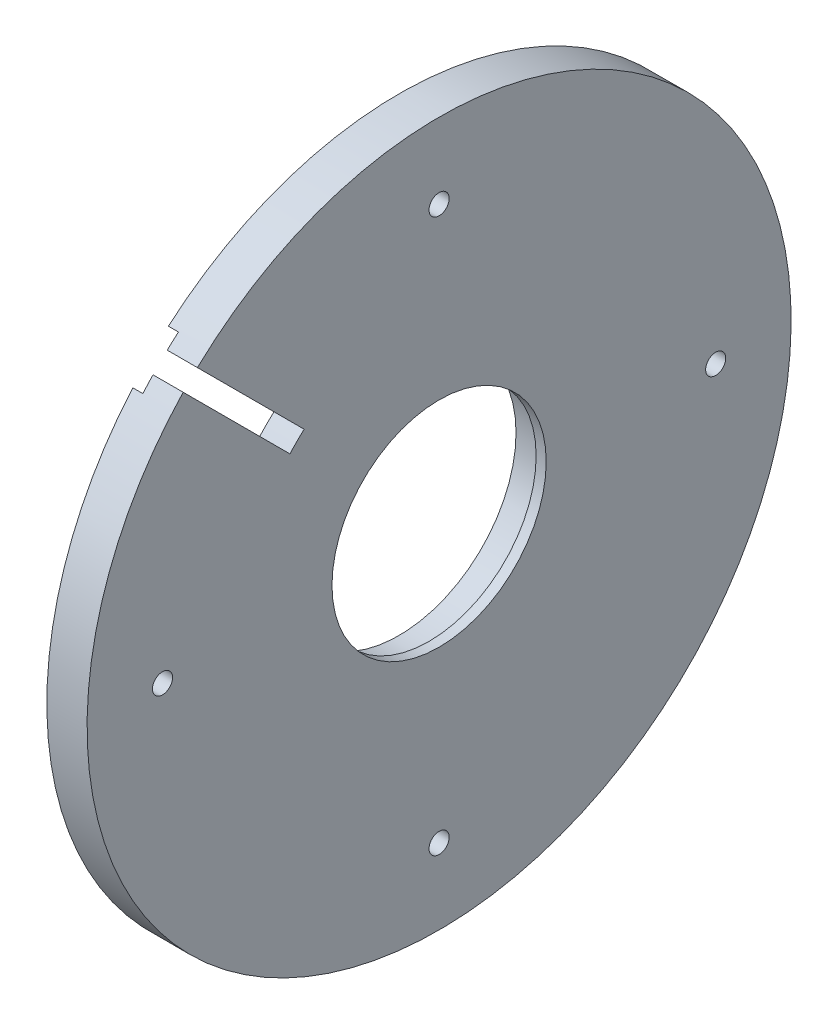
SolidWorks part; units mm, degrees
material "6061 Alloy"
ref_plane "Front Plane" through (0, 0, 0) normal (0, 0, 1) x (1, 0, 0)
ref_plane "Top Plane" through (0, 0, 0) normal (0, 1, 0) x (1, 0, 0)
ref_plane "Right Plane" through (0, 0, 0) normal (1, 0, 0) x (0, 0, -1)
sketch "Sketch1" plane through (0, 0, 0) normal (1, 0, 0) x (0, -0.1678, -0.9858)
  circle A0 centre (-28.5429, 18.9571) radius 11.65
  circle A1 centre (-28.5429, 18.9571) radius 35
  dimension "D1" = 70
extrude "Boss-Extrude1" add sketch "Sketch1" along normal blind 4
sketch "Sketch2" plane through (0, 0, 0) normal (-1, 0, 0) x (0, 0, 1)
  line L6 (38.3756, 38.3083) -> (48.9998, 48.9326)
  line L7 (50.4141, 47.5183) -> (54.0073, 51.1116)
  line L11 (54.0073, 51.1116) -> (51.312, 52.9305)
  line L12 (51.312, 52.9305) -> (48.9998, 48.9326)
  line L13 (39.7898, 36.8941) -> (50.4141, 47.5183)
  arc A2 (39.7898, 36.8941) -> (38.3756, 38.3083) centre (24.9582, 23.4767) ccw
extrude "Cut-Extrude1" cut sketch "Sketch2" against normal blind 10
sketch "Sketch6" plane through (4, 0, 0) normal (1, 0, 0) x (0, 0, -1)
  line L0 (-24.9582, 23.4767) -> (10.0418, 23.4767) construction
  arc A0 (-50.404, 47.5082) -> (-48.9897, 48.9225) centre (-24.9582, 23.4767) ccw construction
  circle A1 centre (-24.9582, -4.0233) radius 1
  circle A2 centre (2.5418, 23.4767) radius 1
  circle A3 centre (-52.4582, 23.4767) radius 1
  circle A4 centre (-24.9582, 50.9767) radius 1
  dimension "D1" = 4
extrude "Cut-Extrude4" cut sketch "Sketch6" against normal blind 10
sketch "Sketch7" plane through (4, 0, 0) normal (-1, 0, 0) x (0, 0, 1)
  circle A1 centre (24.9582, 23.4767) radius 11.65
  circle A2 centre (24.9582, 23.4767) radius 10.65
extrude "Boss-Extrude3" add sketch "Sketch7" along normal blind 1
sketch "Sketch8" plane through (3, 0, 0) normal (-1, 0, 0) x (0, 0, 1)
  circle A0 centre (24.9582, 23.4767) radius 11.65
  circle A1 centre (24.9582, 23.4767) radius 11.15
  dimension "D1" = 0.5
extrude "Cut-Extrude5" cut sketch "Sketch8" against normal blind 0.25
fillet "Fillet1" radius 0.1 1 edges at (3.25, 23.4767, 36.1082)
sketch "Sketch9" plane through (0, 0, 0) normal (-1, 0, 0) x (0, 0, 1)
  line L0 (48.9897, 48.9225) -> (50.404, 47.5082)
  line L1 (50.404, 47.5082) -> (40.4029, 37.5072)
  line L3 (38.9887, 38.9215) -> (48.9897, 48.9225)
  line L4 (36.2542, 38.3083) -> (48.9897, 51.0438)
  line L5 (48.9897, 51.0438) -> (52.5253, 47.5082)
  line L6 (52.5253, 47.5082) -> (39.7898, 34.7727)
  line L7 (36.2542, 38.3083) -> (35.5471, 37.6012)
  line L8 (39.7898, 34.7727) -> (36.2542, 38.3083) construction
  line L9 (35.5471, 37.6012) -> (39.0827, 34.0656)
  line L10 (39.7898, 34.7727) -> (39.0827, 34.0656)
  line L11 (38.9887, 38.9215) -> (40.4029, 37.5072)
  line L12 (38.3756, 38.3083) -> (48.9897, 48.9225) construction
  line L13 (39.7898, 36.8941) -> (38.3756, 38.3083) construction
  line L14 (50.404, 47.5082) -> (39.7898, 36.8941) construction
  dimension "D2" = 1
  dimension "D1" = 1.5
extrude "Cut-Extrude6" cut sketch "Sketch9" against normal blind 1
